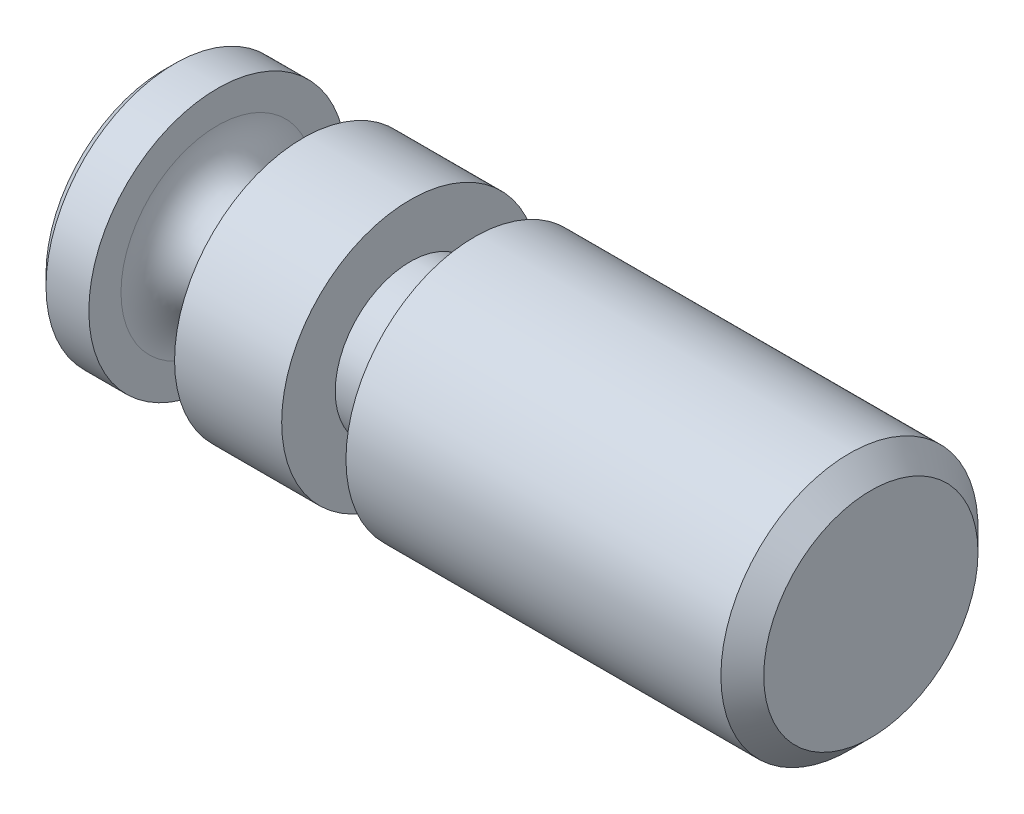
SolidWorks part; units mm, degrees
ref_plane "Plan de face" through (0, 0, 0) normal (0, 0, 1) x (1, 0, 0)
ref_plane "Plan de dessus" through (0, 0, 0) normal (0, 1, 0) x (1, 0, 0)
ref_plane "Plan de droite" through (0, 0, 0) normal (1, 0, 0) x (0, 0, -1)
sketch "Esquisse1" plane through (0, 0, 0) normal (0, 0, 1) x (1, 0, 0)
  line L0 (-17.5, 6) -> (0, 6) construction
  line L1 (0, 0) -> (-17.5, 0)
  line L4 (-17.5, 0) -> (-17.5, 2.5)
  line L5 (-17.5, 6) -> (-20.5, 6) construction
  line L14 (-17.5, 2.5) -> (-20.5, 2.5)
  line L19 (-17.5, 6) -> (-20.5, 2.5) construction
  line L23 (-25.5, 0) -> (-20.5, 0)
  line L24 (-20.5, 0) -> (-20.5, 2.5)
  line L26 (1, 6) -> (1, 1)
  line L27 (1, 1) -> (0, 0)
  line L28 (0, 6) -> (1, 6) construction
  line L29 (-20.5, 6) -> (-25.5, 6) construction
  line L31 (-25.5, 6) -> (-29.5, 6) construction
  line L35 (-31.5, 0) -> (-29.5, 0)
  line L36 (-29.5, 0) -> (-29.5, 1.5)
  line L38 (-32, 6) -> (-32, 0.5)
  line L39 (-32, 0.5) -> (-31.5, 0)
  line L40 (-29.5, 6) -> (-31.5, 6) construction
  line L41 (-31.5, 6) -> (-32, 6) construction
  line L43 (-32, 6) -> (1, 6)
  line L44 (-25.5, 1.5) -> (-29.5, 1.5) construction
  line L46 (-25.5, 1.5) -> (-25.5, 0)
  arc A1 (-25.5, 1.5) -> (-29.5, 1.5) centre (-27.5, 1.5) ccw
  dimension "D1" = 17.5
  dimension "D6" = 1
  dimension "D9" = 4
  dimension "D11" = 0.5
  dimension "D12" = 45
  dimension "D13" = 4.5
revolve "Révolution2" add sketch "Esquisse1" angle 360 about L43
